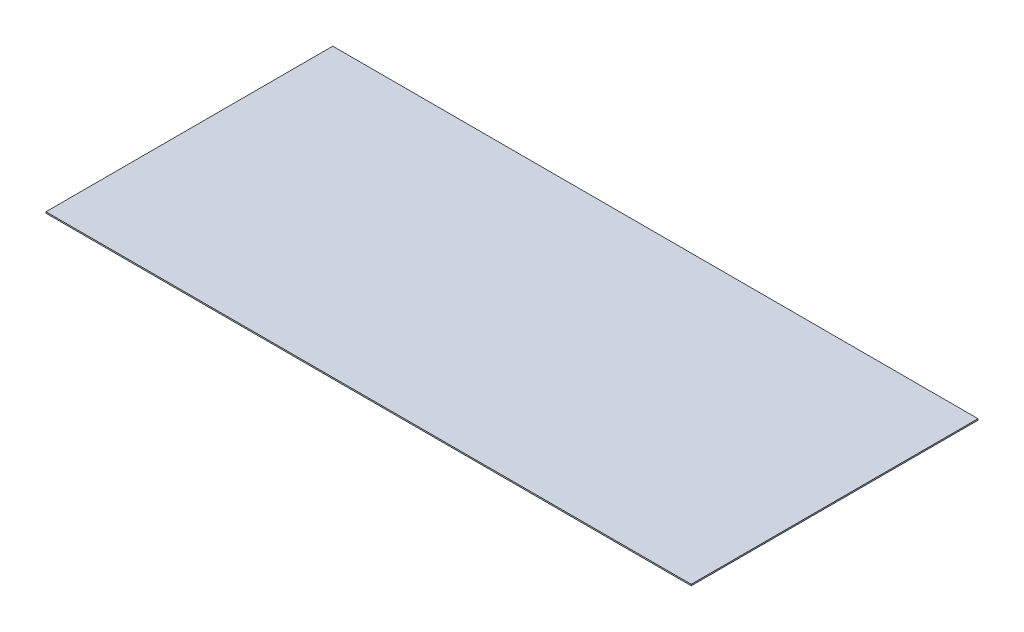
SolidWorks part; units mm, degrees
ref_plane "Alzado" through (0, 0, 0) normal (0, 0, 1) x (1, 0, 0)
ref_plane "Planta" through (0, 0, 0) normal (0, 1, 0) x (1, 0, 0)
ref_plane "Vista lateral" through (0, 0, 0) normal (1, 0, 0) x (0, 0, -1)
sketch "Croquis1" plane through (0, 0, 0) normal (0, 1, 0) x (1, 0, 0)
  line L1 (-450, 200) -> (450, 200)
  line L2 (-450, 200) -> (-450, -200)
  line L3 (-450, -200) -> (450, -200)
  line L4 (450, 200) -> (450, -200)
  line L5 (-450, 200) -> (450, -200) construction
  line L6 (-450, -200) -> (450, 200) construction
  point P0 (0, 0)
  dimension "D1" = 900
  dimension "D2" = 400
extrude "Saliente-Extruir1" add sketch "Croquis1" along normal blind 1.9
